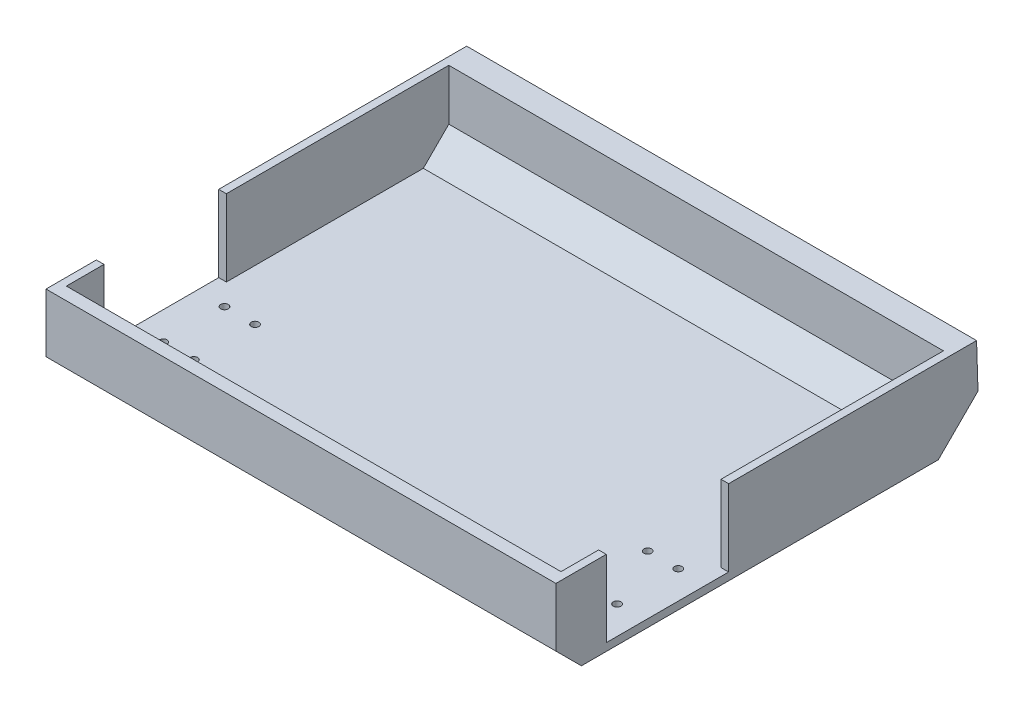
SolidWorks part; units mm, degrees
material "ABS"
ref_plane "Alzado" through (0, 0, 0) normal (0, 0, 1) x (1, 0, 0)
ref_plane "Planta" through (0, 0, 0) normal (0, 1, 0) x (1, 0, 0)
ref_plane "Vista lateral" through (0, 0, 0) normal (1, 0, 0) x (0, 0, -1)
sketch "Croquis1" plane through (0, 0, 0) normal (0, 1, 0) x (1, 0, 0)
  line L1 (0, 0) -> (200, 0)
  line L2 (0, 0) -> (0, 150)
  line L3 (0, 150) -> (200, 150)
  line L4 (200, 0) -> (200, 150)
  dimension "D1" = 150
  dimension "D2" = 200
extrude "Saliente-Extruir1" add sketch "Croquis1" along normal blind 3
sketch "Croquis2" plane through (0, 3, 0) normal (0, 1, 0) x (1, 0, 0)
  line L0 (0, 0) -> (200, 0) construction
  line L1 (0, 150) -> (3, 150)
  line L2 (0, 150) -> (0, 0)
  line L3 (0, 0) -> (3, 0)
  line L4 (3, 150) -> (3, 0)
  line L6 (200, 150) -> (197, 150)
  line L7 (200, 150) -> (200, 0)
  line L8 (200, 0) -> (197, 0)
  line L9 (197, 150) -> (197, 0)
  dimension "D1" = 3
  dimension "D2" = 3
extrude "Saliente-Extruir2" add sketch "Croquis2" along normal blind 30
sketch "Croquis5" plane through (0, 0, 0) normal (0, 0, 1) x (1, 0, 0)
  line L0 (0, 33) -> (3, 33)
  line L1 (3, 33) -> (200, 33)
  line L2 (200, 33) -> (200, 0)
  line L3 (200, 0) -> (0, 0)
  line L4 (0, 0) -> (0, 33)
extrude "Saliente-Extruir4" add sketch "Croquis5" along normal blind 5
sketch "Croquis6" plane through (0, 0, -150) normal (0, 0, -1) x (-1, 0, 0)
  line L0 (-200, 33) -> (0, 33)
  line L1 (0, 33) -> (0, 0)
  line L2 (0, 0) -> (-200, 0)
  line L3 (-200, 0) -> (-200, 33)
extrude "Saliente-Extruir5" add sketch "Croquis6" along normal blind 5
chamfer "Chaflán1" distance 10 angle 45 2 edges at (100, 0, 5) (100, 0, -155)
chamfer "Chaflán2" distance 10 angle 45 2 edges at (100, 3, 0) (100, 3, -150)
sketch "Croquis7" plane through (0, 3, 0) normal (0, 1, 0) x (1, 0, 0)
  line L0 (200, -5) -> (200, 155) construction
  line L1 (0, 155) -> (0, -5) construction
  line L2 (200, -5) -> (0, -5) construction
  circle A0 centre (189, 30) radius 1.5
  circle A1 centre (177, 30) radius 1.5
  circle A2 centre (189, 54) radius 1.5
  circle A3 centre (177, 54) radius 1.5
  circle A4 centre (23, 30) radius 1.5
  circle A5 centre (11, 30) radius 1.5
  circle A6 centre (23, 54) radius 1.5
  circle A7 centre (11, 54) radius 1.5
  point P8 (0, 0)
  point P9 (0, 0)
  point P10 (0, 0)
  point P11 (0, 0)
  point P24 (0, 0)
  dimension "D1" = 3
  dimension "D2" = 12
  dimension "D3" = 24
  dimension "D6" = 11
  dimension "D4" = 12
  dimension "D5" = 11
  dimension "D7" = 35
extrude "Cortar-Extruir2" cut sketch "Croquis7" against normal blind 10
sketch "Croquis8" plane through (200, 0, 0) normal (1, 0, 0) x (0, 0, -1)
  line L0 (14.75, 33) -> (14.75, 3)
  line L1 (-5, 33) -> (155, 33) construction
  line L2 (14.75, 3) -> (62.75, 3)
  line L3 (62.75, 3) -> (62.75, 33)
  line L4 (62.75, 33) -> (14.75, 33)
  line L5 (-5, 10) -> (-5, 33) construction
  line L6 (5, 0) -> (145, 0) construction
  dimension "D1" = 19.75
  dimension "D2" = 48
  dimension "D3" = 3
extrude "Cortar-Extruir3" cut sketch "Croquis8" against normal blind 200
sketch "Croquis9" plane through (200, 0, 0) normal (1, 0, 0) x (0, 0, -1)
  line L5 (155, 33) -> (160, 33)
  line L6 (160, 33) -> (160.5603, 15.5603)
  line L8 (155, 33) -> (155, 10)
  line L9 (155, 10) -> (160.5603, 15.5603)
  line L11 (145, 0) -> (151.4162, 6.4162)
  line L12 (145, 0) -> (155, 10) construction
  line L13 (5, 0) -> (145, 0) construction
  line M11 (155, 10) -> (155, 33)
  dimension "D1" = 135
  dimension "D2" = 5
  dimension "D3" = 268.16
extrude "Saliente-Extruir6" add sketch "Croquis9" against normal blind 200 contours L9 L6 L5 M11
